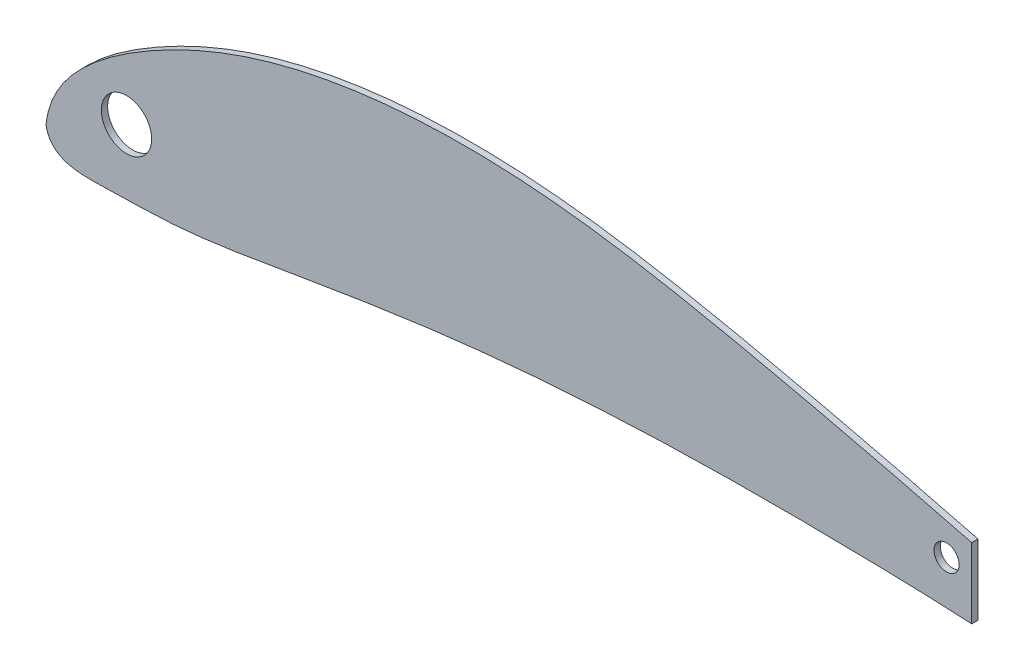
SolidWorks part; units mm, degrees
material "Balsa"
ref_plane "Front Plane" through (0, 0, 0) normal (0, 0, 1) x (1, 0, 0)
ref_plane "Top Plane" through (0, 0, 0) normal (0, 1, 0) x (1, 0, 0)
ref_plane "Right Plane" through (0, 0, 0) normal (1, 0, 0) x (0, 0, -1)
sketch "Sketch1" plane through (0, 0, 0) normal (0, 0, 1) x (1, 0, 0)
  spline S0 degree 3 poles (0.0006, 0.0001) (0.8106, 7.3592) (8.6491, 17.8566) (26.2867, 29.9752) (52.1111, 42.0692) (89.5976, 49.2908) (131.4008, 47.8848) (173.2567, 40.0411) (217.9611, 29.613) (256.9521, 19.5289) (290.3598, 8.711) (301.2732, 4.3828) (314.8169, -0.5162) (309.8463, 0.0001) knots 0 0 0 0 0.060864 0.113688 0.188609 0.312909 0.448482 0.557612 0.691544 0.852438 0.929756 0.976058 1 1 1 1
  spline S1 degree 3 poles (309.8463, 0.0001) (303.9568, 1.471) (293.9895, 2.094) (276.264, 4.5144) (260.8463, 5.4274) (235.8588, 7.8703) (205.1014, 8.8381) (157.7186, 9.0307) (110.4973, 6.1815) (66.5062, -0.5867) (36.4547, -6.0985) (15.3166, -6.1891) (1.2307, -6.9241) (0.0006, 0.0001) knots 0 0 0 0 0.057787 0.095275 0.171021 0.205339 0.335319 0.464904 0.658702 0.785512 0.893517 0.943092 1 1 1 1
extrude "Boss-Extrude1" add sketch "Sketch1" along normal blind 1.5875
sketch "Sketch2" plane through (0, 0, 1.5875) normal (0, 0, 1) x (1, 0, 0)
  circle A0 centre (20.32, 10.16) radius 6.35
  circle A1 centre (227.2963, 19.0501) radius 3.175
  dimension "D2" = 12.7
  dimension "D3" = 6.35
  dimension "D6" = 20.32
  dimension "D1" = 82.55
  dimension "D4" = 19.05
  dimension "D5" = 10.16
extrude "Cut-Extrude1" cut sketch "Sketch2" against normal through all
sketch "Sketch3" plane through (0, 0, 1.5875) normal (0, 0, 1) x (1, 0, 0)
  line L1 (350.4863, -6.3499) -> (233.6463, -6.3499)
  line L2 (350.4863, -6.3499) -> (350.4863, 44.4501)
  line L3 (350.4863, 44.4501) -> (233.6463, 44.4501)
  line L4 (233.6463, -6.3499) -> (233.6463, 44.4501)
  circle A0 centre (227.2963, 19.0501) radius 3.175 construction
  dimension "D1" = 6.35
  dimension "D2" = 116.84
  dimension "D3" = 50.8
  dimension "D4" = 44.45
extrude "Cut-Extrude2" cut sketch "Sketch3" against normal through all contours L3 L4 L1 L2
